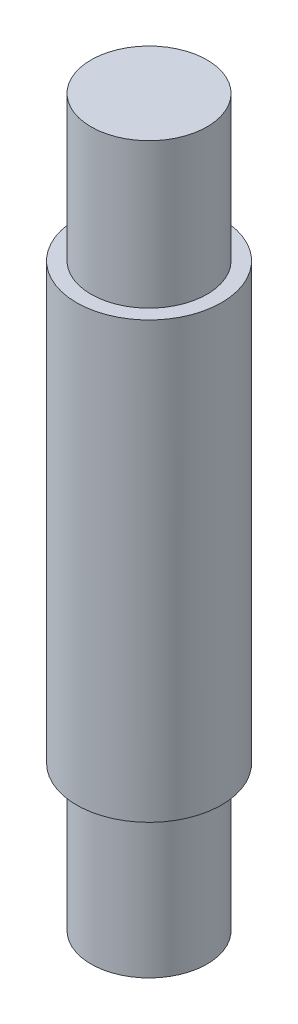
SolidWorks part; units mm, degrees
material "Acrylic (Medium-high impact)"
ref_plane "Front Plane" through (0, 0, 0) normal (0, 0, 1) x (1, 0, 0)
ref_plane "Top Plane" through (0, 0, 0) normal (0, 1, 0) x (1, 0, 0)
ref_plane "Right Plane" through (0, 0, 0) normal (1, 0, 0) x (0, 0, -1)
sketch "Sketch1" plane through (0, 0, 0) normal (0, 1, 0) x (1, 0, 0)
  circle A0 centre (0, 0) radius 5
  dimension "D1" = 10
extrude "Boss-Extrude1" add sketch "Sketch1" along normal blind 50
sketch "Sketch2" plane through (0, 50, 0) normal (0, 1, 0) x (1, 0, 0)
  circle A0 centre (0, 0) radius 5
  circle A1 centre (0, 0) radius 4
  dimension "D1" = 8
extrude "Cut-Extrude1" cut sketch "Sketch2" against normal blind 10
sketch "Sketch3" plane through (0, 0, 0) normal (0, -1, 0) x (1, 0, 0)
  circle A0 centre (0, 0) radius 5
  circle A1 centre (0, 0) radius 4
  dimension "D1" = 8
extrude "Cut-Extrude2" cut sketch "Sketch3" against normal blind 10
